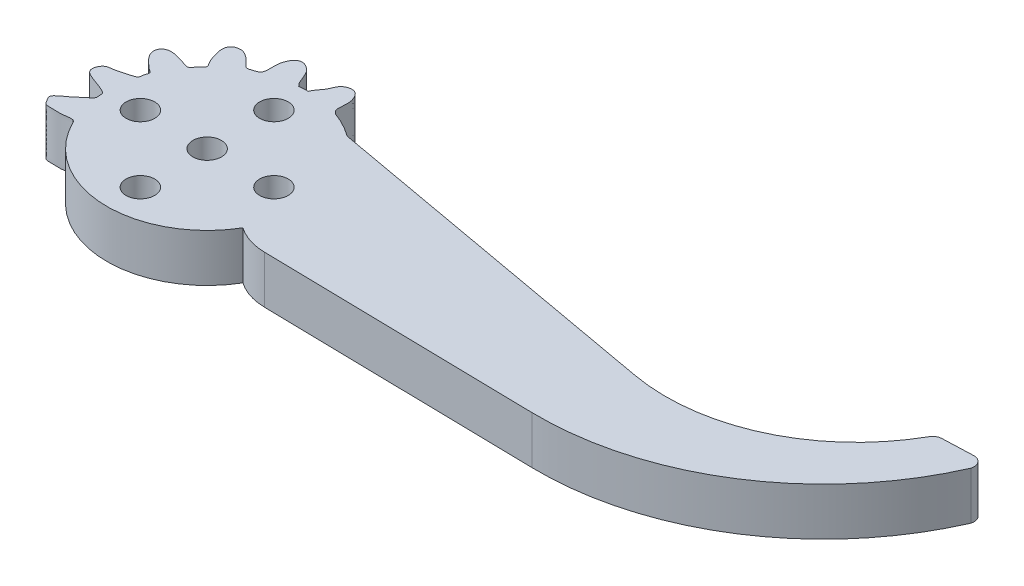
SolidWorks part; units mm, degrees
material "Thornel Mat VMA"
ref_plane "前视基准面" through (0, 0, 0) normal (0, 0, 1) x (1, 0, 0)
ref_plane "上视基准面" through (0, 0, 0) normal (0, 1, 0) x (1, 0, 0)
ref_plane "右视基准面" through (0, 0, 0) normal (1, 0, 0) x (0, 0, -1)
sketch "草图1" plane through (0, 0, 0) normal (0, 1, 0) x (1, 0, 0)
  line L0 (-37.3446, -5.808) -> (-37.2484, -5.9827)
  line L1 (-38.4582, -2.6118) -> (-39.8436, -3.7753)
  line L2 (15.1383, 0.6022) -> (-21.118, 7.1339)
  line L3 (40.1533, 11.075) -> (36.9313, 10.9555)
  line L4 (-15.5076, -7.6284) -> (13.0951, -8.1746)
  arc A0 (-18.8224, -6.5528) -> (-15.5076, -7.6284) centre (-15.393, -1.6294) ccw
  arc A1 (-37.2484, -5.9827) -> (-18.8224, -6.5528) centre (-27.8799, -1.2414) ccw
  arc A2 (-38.3671, -1.7598) -> (-38.3197, -2.3643) centre (-27.8799, -1.2414) ccw
  arc A3 (-35.3513, 6.1361) -> (-36.1425, 5.2378) centre (-27.8799, -1.2414) ccw
  arc A4 (-27.7909, 9.2583) -> (-28.746, 9.2229) centre (-27.8799, -1.2414) ccw
  arc A5 (-21.6843, 7.2359) -> (-24.2992, 8.6292) centre (-27.8799, -1.2414) ccw
  arc A6 (15.1383, 0.6022) -> (36.0977, 10.448) centre (18.6843, 20.2853) ccw
  arc A7 (36.9313, 10.9555) -> (36.0977, 10.448) centre (36.9684, 9.9561) ccw
  arc A8 (41.1448, 9.7775) -> (40.1533, 11.075) centre (40.1903, 10.0757) ccw
  arc A9 (13.0951, -8.1746) -> (41.1448, 9.7775) centre (13.6679, 21.8199) ccw
  ellipse E0 centre (-39.0174, -2.1254) end of major axis (-38.4514, -2.6039) minor radius 0.7149 (-38.4582, -2.6118) -> (-38.3197, -2.3643) ccw
  spline S0 degree 4 poles (-39.8436, -3.7753) (-40.1394, -3.9585) (-40.6828, -4.4003) (-40.8288, -4.5498) (-40.8989, -4.7751) (-40.8715, -4.9152) (-40.8111, -5.0288) (-40.5713, -5.4058) (-40.4232, -5.6413) (-40.1458, -5.7438) (-39.2232, -5.7259) (-38.7535, -5.797) (-37.7701, -5.5585) (-37.4717, -5.6624) (-37.4081, -5.7267) (-37.3446, -5.808) knots 0 0 0 0 0 0.194273 0.241619 0.282323 0.331388 0.386783 0.447394 0.523863 0.607321 0.701771 0.796544 0.874385 1 1 1 1 1 weights 1 1 1 1 1 1 1 1 1 1 1 1 1 1 1 1
  spline S1 degree 4 poles (-40.3278, 0.9926) (-40.4903, 0.9996) (-40.7132, 0.9189) (-40.9545, 0.6937) (-41.1314, 0.3346) (-41.1903, 0.0568) (-41.1655, -0.2022) (-41.0366, -0.4215) (-40.8162, -0.6003) (-40.4855, -0.7669) (-40.1742, -0.8984) (-39.2577, -1.2205) (-38.5994, -1.4792) (-38.5038, -1.5713) (-38.3671, -1.7598) knots 0 0 0 0 0 0.159646 0.225639 0.29102 0.354612 0.417161 0.480845 0.547969 0.628061 0.718716 0.808353 1 1 1 1 1 weights 1 1 1 1 1 1 1 1 1 1 1 1 1 1 1
  spline S2 degree 4 poles (-36.1425, 5.2378) (-36.317, 5.087) (-36.3648, 5.1642) (-37.2776, 5.3613) (-37.9424, 5.6325) (-38.6331, 5.7199) (-38.9165, 5.6536) (-39.2253, 5.5209) (-39.4263, 5.3223) (-39.5479, 5.0659) (-39.5684, 4.735) (-39.5249, 4.4589) (-39.1679, 3.873) (-38.7405, 3.4666) (-38.2547, 3.0073) (-37.8904, 2.7774) (-37.6568, 2.6484) (-37.9695, 2.0748) (-37.8972, 1.785) (-38.165, 1.4058) (-38.7694, 1.4552) (-39.3069, 1.0969) (-40.3278, 0.9926) knots 0 0 0 0 0 0.10255 0.155534 0.209165 0.256715 0.297928 0.33452 0.370937 0.407253 0.448167 0.495157 0.547295 0.600813 0.648484 0.693866 0.734505 0.772382 0.811633 0.850282 1 1 1 1 1 weights 1 1 1 1 1 1 1 1 1 1 1 1 1 1 1 1 1 1 1 1 1 1 1
  spline S3 degree 4 poles (-28.746, 9.2229) (-29.0669, 9.5632) (-29.0038, 9.4956) (-29.5148, 10.8685) (-29.9052, 11.2238) (-30.3462, 11.5383) (-30.7753, 11.6478) (-31.1569, 11.5387) (-31.4638, 11.2134) (-31.7058, 10.7908) (-31.8347, 10.2773) (-31.8664, 9.945) (-31.836, 8.7702) (-31.9863, 8.469) (-32.3984, 8.3298) (-33.0125, 8.105) (-33.2833, 8.1264) (-33.8799, 8.9557) (-34.6807, 9.4543) (-35.0628, 9.5553) (-35.588, 9.4783) (-35.9641, 9.2369) (-36.1471, 8.8591) (-36.1461, 8.3295) (-36.0313, 7.8055) (-35.6223, 6.4483) (-35.3269, 6.4953) (-35.3513, 6.1361) knots 0 0 0 0 0 0.095392 0.134992 0.173691 0.207189 0.240204 0.27329 0.306895 0.341656 0.381579 0.419994 0.457685 0.496014 0.5279 0.564801 0.606645 0.647352 0.689606 0.727606 0.760626 0.793889 0.827476 0.866012 0.906298 1 1 1 1 1 weights 1 1 1 1 1 1 1 1 1 1 1 1 1 1 1 1 1 1 1 1 1 1 1 1 1 1 1 1
  spline S4 degree 4 poles (-24.2992, 8.6292) (-24.5328, 8.9247) (-24.7681, 8.6855) (-24.5785, 10.1901) (-24.6546, 10.6217) (-24.8037, 11.1232) (-25.0532, 11.5002) (-25.3827, 11.7413) (-25.8051, 11.7638) (-26.234, 11.6289) (-26.6025, 11.3608) (-26.8008, 10.9925) (-27.0321, 10.2974) (-27.3826, 9.9958) (-27.7026, 9.5074) (-27.7909, 9.2583) knots 0 0 0 0 0 0.16745 0.239586 0.313308 0.377038 0.439844 0.502444 0.564992 0.628373 0.693637 0.759108 0.826532 1 1 1 1 1 weights 1 1 1 1 1 1 1 1 1 1 1 1 1 1 1 1
  spline S5 degree 3 poles (-21.118, 7.1339) (-21.2124, 7.1471) (-21.3065, 7.1623) (-21.4954, 7.1964) (-21.59, 7.2154) (-21.6843, 7.2359) knots 0 0 0 0 0.497064 0.497064 1 1 1 1 weights 1 1 1 1 1 1
extrude "凸台-拉伸1" add sketch "草图1" along normal blind 5
sketch "草图2" plane through (0, 5, 0) normal (0, 1, 0) x (1, 0, 0)
  line L0 (-27.8799, -1.2414) -> (-27.8799, 16.6915) construction
  line L1 (-27.8799, -1.2414) -> (-11.2305, -1.2414) construction
  circle A0 centre (-27.8799, -1.2414) radius 7 construction
  circle A1 centre (-27.8799, -1.2414) radius 1.5
  circle A2 centre (-27.8799, 5.7586) radius 1.5
  circle A3 centre (-20.8799, -1.2414) radius 1.5
  circle A4 centre (-27.8799, -8.2414) radius 1.5
  circle A5 centre (-34.8799, -1.2414) radius 1.5
  dimension "D1" = 14
  dimension "D2" = 3
  dimension "D3" = 3
  dimension "D4" = 3
extrude "切除-拉伸1" cut sketch "草图2" against normal blind 10
